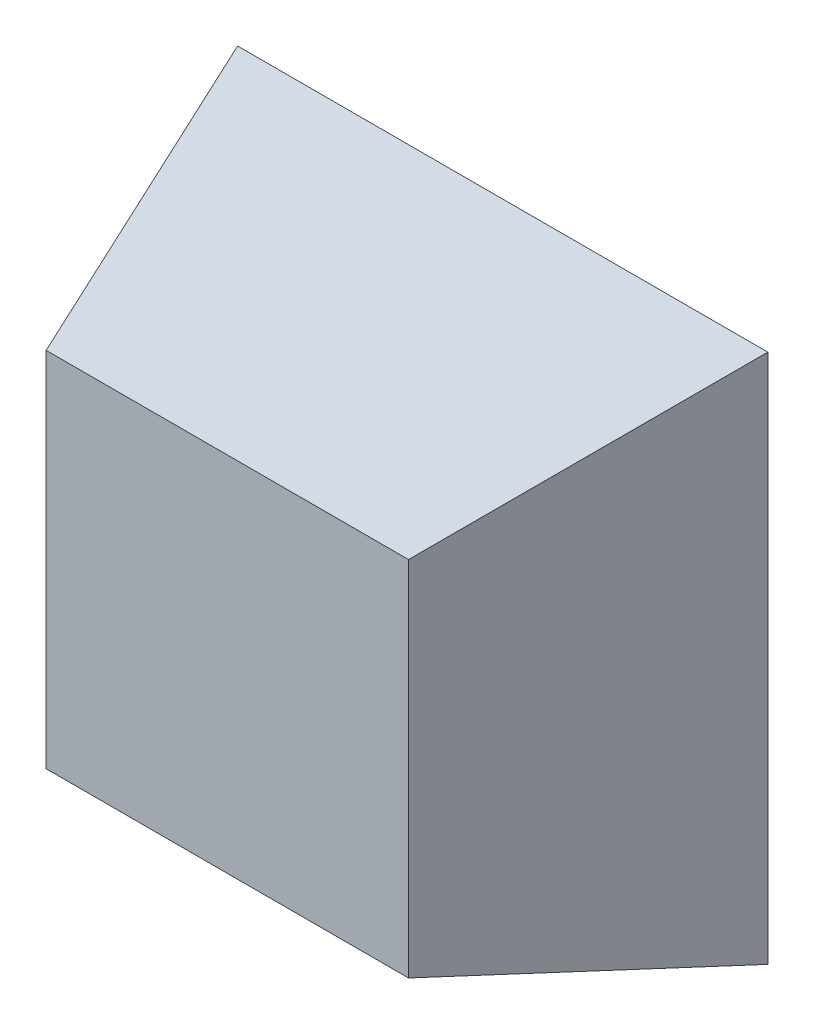
SolidWorks part; units mm, degrees
ref_plane "Front Plane" through (0, 0, 0) normal (0, 0, 1) x (1, 0, 0)
ref_plane "Top Plane" through (0, 0, 0) normal (0, 1, 0) x (1, 0, 0)
ref_plane "Right Plane" through (0, 0, 0) normal (1, 0, 0) x (0, 0, -1)
sketch "Sketch1" plane through (0, 0, 0) normal (0, 0, 1) x (1, 0, 0)
  line L1 (-9.05, 9.05) -> (9.05, 9.05)
  line L2 (-9.05, 9.05) -> (-9.05, -9.05)
  line L3 (-9.05, -9.05) -> (9.05, -9.05)
  line L4 (9.05, 9.05) -> (9.05, -9.05)
  line L5 (0, -9.05) -> (0, 9.05) construction
  line L6 (-9.05, 0) -> (9.05, 0) construction
  line L7 (-7.05, 7.05) -> (7.05, 7.05) construction
  line L8 (-7.05, 7.05) -> (-7.05, -7.05) construction
  line L9 (-7.05, -7.05) -> (7.05, -7.05) construction
  line L10 (7.05, 7.05) -> (7.05, -7.05) construction
  line L11 (0, -7.05) -> (0, 7.05) construction
  line L12 (-7.05, 0) -> (7.05, 0) construction
  point P0 (0, 0)
  point P4 (0, 0)
  dimension "D1" = 18.1
  dimension "D2" = 18.1
  dimension "D3" = 2
  dimension "D4" = 2
ref_plane "Plane1" through (0, 0, 9.4) normal (0, 0, 1) x (1, 0, 0)
sketch "Sketch2" plane through (0, 0, 9.4) normal (0, 0, 1) x (1, 0, 0)
  line L1 (-6.185, 6.185) -> (6.185, 6.185)
  line L2 (-6.185, 6.185) -> (-6.185, -6.185)
  line L3 (-6.185, -6.185) -> (6.185, -6.185)
  line L4 (6.185, 6.185) -> (6.185, -6.185)
  line L5 (0, -6.185) -> (0, 6.185) construction
  line L6 (-6.185, 0) -> (6.185, 0) construction
  line L7 (-4.585, 4.585) -> (4.585, 4.585) construction
  line L8 (-4.585, 4.585) -> (-4.585, -4.585) construction
  line L9 (-4.585, -4.585) -> (4.585, -4.585) construction
  line L10 (4.585, 4.585) -> (4.585, -4.585) construction
  line L11 (0, -4.585) -> (0, 4.585) construction
  line L12 (-4.585, 0) -> (4.585, 0) construction
  point P0 (0, 0)
  point P4 (0, 0)
  dimension "D1" = 12.37
  dimension "D2" = 12.37
  dimension "D3" = 1.6
  dimension "D4" = 1.6
loft "Loft2" add profiles "Sketch1", "Sketch2"
sketch "Sketch4" plane through (0, 0, 0) normal (0, 1, 0) x (1, 0, 0)
  line L0 (-6.185, -9.4) -> (6.185, -9.4)
  line L1 (-9.9551, -9.4) -> (9.9551, -9.4) construction
  line L2 (9.05, 0) -> (6.185, -9.4) construction
  line L3 (-9.05, 0) -> (-6.185, -9.4) construction
  spline S0 degree 2 poles (-6.185, -9.4) (0, -7.8931) (6.185, -9.4) knots 0 0 0 1 1 1
shell "Shell4" thickness 2.5
ref_plane "Plane2" through (0, 0, -4) normal (0, 0, 1) x (1, 0, 0)
sketch "Sketch5" plane through (0, 0, -4) normal (0, 0, 1) x (1, 0, 0)
  line L1 (-2.9, 2) -> (2.9, 2)
  line L2 (-2.9, 2) -> (-2.9, -2)
  line L3 (-2.9, -2) -> (2.9, -2)
  line L4 (2.9, 2) -> (2.9, -2)
  line L5 (0, -2) -> (0, 2) construction
  line L6 (-2.9, 0) -> (2.9, 0) construction
  point P0 (0, 0)
  dimension "D1" = 5.8
  dimension "D2" = 4
extrude "Boss-Extrude1" add sketch "Sketch5" along normal up to surface (10.9 mm away) up to face at (0, 0, 6.9)
sketch "Sketch6" plane through (0, 0, -4) normal (0, 0, -1) x (-1, 0, 0)
  line L0 (0, -2.15) -> (0, 2.15) construction
  line L1 (2.15, 0) -> (-2.15, 0) construction
  line L2 (0.73, 2.15) -> (-0.73, 2.15)
  line L3 (-0.73, 2.15) -> (-0.73, 0.73)
  line L4 (-0.73, 0.73) -> (-2.15, 0.73)
  line L5 (-2.15, 0.73) -> (-2.15, -0.73)
  line L6 (-0.73, -0.73) -> (-2.15, -0.73)
  line L7 (-0.73, -2.15) -> (-0.73, -0.73)
  line L8 (0.73, -2.15) -> (-0.73, -2.15)
  line L9 (0.73, -2.15) -> (0.73, -0.73)
  line L10 (0.73, -0.73) -> (2.15, -0.73)
  line L11 (2.15, 0.73) -> (2.15, -0.73)
  line L12 (0.73, 0.73) -> (2.15, 0.73)
  line L13 (0.73, 2.15) -> (0.73, 0.73)
  point P12 (0, 0)
  dimension "D1" = 2.15
  dimension "D2" = 2.15
  dimension "D3" = 0.73
  dimension "D4" = 0.73
extrude "Cut-Extrude3" cut sketch "Sketch6" against normal blind 4
sketch "Sketch7" plane through (0, -8.2808, 2.5239) normal (0, -0.9566, 0.2915) x (1, 0, 0)
  line L0 (0, 2.7658) -> (0, 0) construction
  line L1 (-6, 5.7658) -> (6, 5.7658)
  line L2 (-6, 5.7658) -> (-6, -0.2342)
  line L3 (-6, -0.2342) -> (6, -0.2342)
  line L4 (6, 5.7658) -> (6, -0.2342)
  line L5 (-6, 5.7658) -> (6, -0.2342) construction
  line L6 (-6, -0.2342) -> (6, 5.7658) construction
  point P4 (0, 2.7658)
  dimension "D1" = 12
  dimension "D2" = 6
extrude "Cut-Extrude4" cut sketch "Sketch7" against normal blind 0.3
